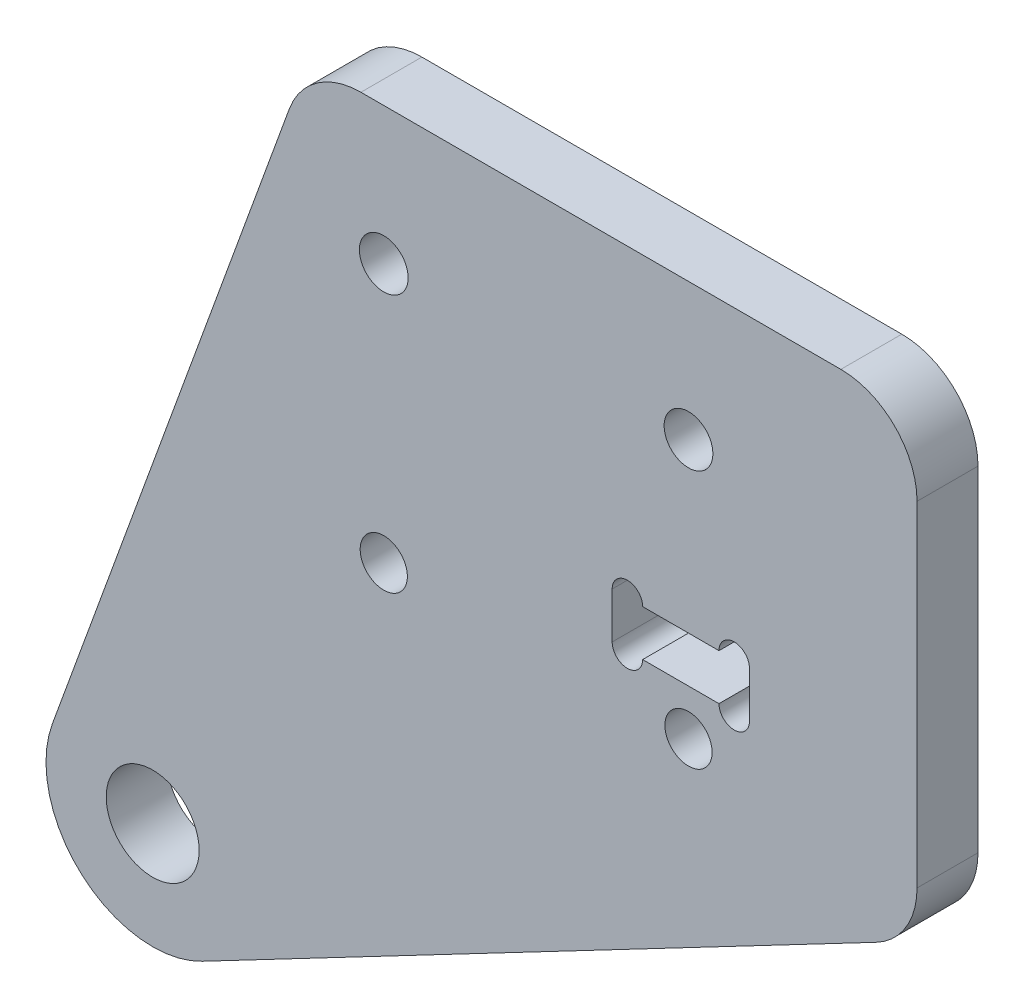
SolidWorks part; units mm, degrees
material "Thornel Mat VMA"
ref_plane "前视基准面" through (0, 0, 0) normal (0, 0, 1) x (1, 0, 0)
ref_plane "上视基准面" through (0, 0, 0) normal (0, 1, 0) x (1, 0, 0)
ref_plane "右视基准面" through (0, 0, 0) normal (1, 0, 0) x (0, 0, -1)
sketch "草图1" plane through (0, 0, 0) normal (0, 0, 1) x (1, 0, 0)
  line L0 (0, 0) -> (40, 0)
  line L1 (40, -30) -> (-22.9301, -63)
  line L2 (-22.9301, -63) -> (0, 0)
  line L3 (5, -9) -> (55.6667, -9) construction
  line L5 (40, 0) -> (40, -30)
  circle A0 centre (5, -9) radius 1.6
  circle A1 centre (25, -9) radius 1.6
  dimension "D3" = 3.2
  dimension "D1" = 9
  dimension "D2" = 20
  dimension "D4" = 15
  dimension "D5" = 63
  dimension "D6" = 110
  dimension "D7" = 30
  dimension "D8" = 40
extrude "凸台-拉伸1" add sketch "草图1" along normal blind 4
fillet "圆角1" radius 7 1 edges at (-22.9301, -63, 2)
sketch "草图2" plane through (0, 0, 4) normal (0, 0, 1) x (1, 0, 0)
  circle A0 centre (-10.1683, -48.4037) radius 3.05
  dimension "D1" = 6.1
extrude "切除-拉伸1" cut sketch "草图2" against normal blind 5.5
sketch "草图3" [suppressed] plane through (0, 0, 4) normal (0, 0, 1) x (1, 0, 0)
  circle A0 centre (-19.8205, -48.3302) radius 4
  arc A1 (-25.8827, -44.8302) -> (-17.0743, -54.769) centre (-19.8205, -48.3302) ccw construction
  dimension "D1" = 8
extrude "切除-拉伸2" [suppressed] cut sketch "草图3" against normal blind 5.5
fillet "圆角2" radius 5 3 edges at (40, -30, 2) (40, 0, 2) (0, 0, 2)
sketch "草图4" plane through (0, 0, 0) normal (0, 0, -1) x (-1, 0, 0)
  line L0 (-40, -26.9762) -> (-40, -5) construction
  line L1 (0, -23) -> (-19.99, -23) construction
  line L2 (0, -23) -> (0, -29) construction
  line L3 (0, -29) -> (-40, -29) construction
  line L4 (-40, -23) -> (-40, -29) construction
  line L5 (-15, -26) -> (-35, -26) construction
  line L6 (-21.99, -23) -> (-27, -23) construction
  line L7 (-21.99, -23) -> (-27, -23)
  line L8 (-19.99, -23) -> (-19.99, -19.99)
  line L9 (-21.99, -19.99) -> (-27, -19.99)
  line L10 (-29, -23) -> (-29, -19.99)
  line L11 (-29, -23) -> (-40, -23) construction
  circle A0 centre (-25, -26) radius 1.55
  circle A1 centre (-5, -26) radius 1.55
  circle A2 centre (-35, -26) radius 1.55 construction
  circle A3 centre (-15, -26) radius 1.55 construction
  arc A4 (-19.99, -19.99) -> (-21.99, -19.99) centre (-20.99, -19.99) ccw
  arc A5 (-21.99, -23) -> (-19.99, -23) centre (-20.99, -23) ccw
  arc A6 (-27, -19.99) -> (-29, -19.99) centre (-28, -19.99) ccw
  arc A7 (-29, -23) -> (-27, -23) centre (-28, -23) ccw
  dimension "D1" = 3.1
  dimension "D10" = 2
  dimension "D2" = 40
  dimension "D3" = 3
  dimension "D4" = 6
  dimension "D5" = 20
  dimension "D6" = 5
  dimension "D7" = 3.01
  dimension "D8" = 9.01
  dimension "D9" = 11
  dimension "D11" = 9.01
extrude "切除-拉伸3" cut sketch "草图4" against normal blind 5
